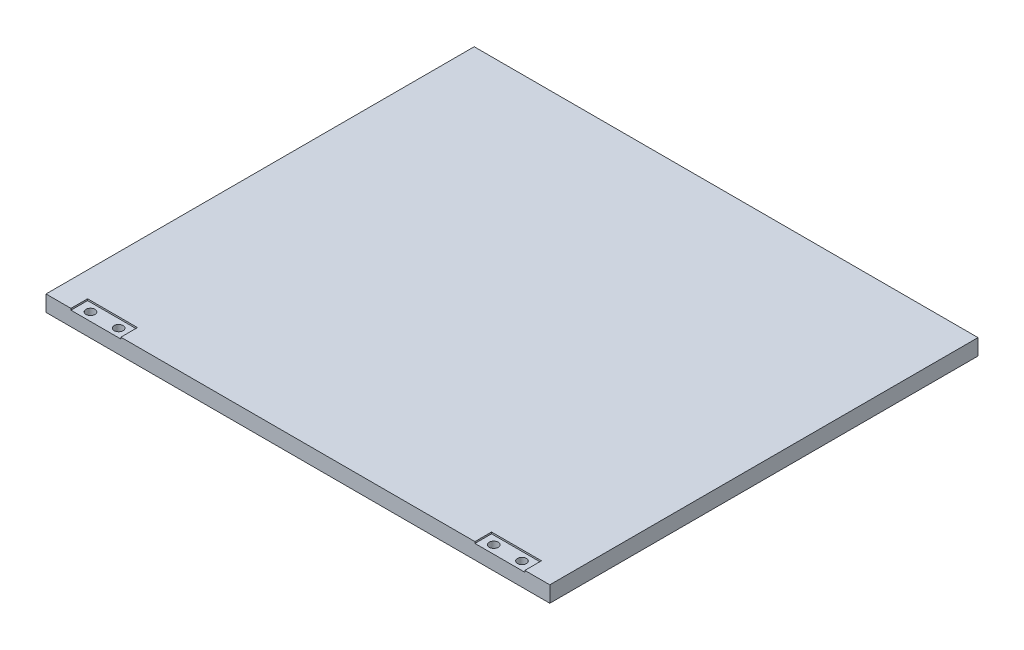
SolidWorks part; units mm, degrees
material "1023 Carbon Steel Sheet (SS)"
ref_plane "Front Plane" through (0, 0, 0) normal (0, 0, 1) x (1, 0, 0)
ref_plane "Top Plane" through (0, 0, 0) normal (0, 1, 0) x (1, 0, 0)
ref_plane "Right Plane" through (0, 0, 0) normal (1, 0, 0) x (0, 0, -1)
sketch "Sketch1" plane through (0, 0, 0) normal (0, 1, 0) x (1, 0, 0)
  line L1 (-100, -85) -> (100, -85)
  line L2 (-100, -85) -> (-100, 85)
  line L3 (-100, 85) -> (100, 85)
  line L4 (100, -85) -> (100, 85)
  line L5 (-100, -85) -> (100, 85) construction
  line L6 (-100, 85) -> (100, -85) construction
  point P0 (0, 0)
  dimension "D1" = 200
  dimension "D2" = 170
extrude "1/4\" Steel Plate" add sketch "Sketch1" along normal blind 6.35
ref_plane "Midplane" through (0, 0, 0) normal (-1, 0, 0) x (0, 0, 1)
sketch "Sketch2" plane through (0, 6.35, 0) normal (0, 1, 0) x (1, 0, 0)
  line L0 (-100, -85) -> (100, -85) construction
  line L1 (-90.094, -85) -> (-70.282, -85)
  line L2 (-90.094, -85) -> (-90.094, -78.396)
  line L3 (-90.094, -78.396) -> (-70.282, -78.396)
  line L4 (-70.282, -85) -> (-70.282, -78.396)
  line L5 (-100, 85) -> (-100, -85) construction
  dimension "D1" = 9.906
  dimension "D2" = 6.604
  dimension "D3" = 19.812
extrude "BladeHingeCut" cut sketch "Sketch2" against normal blind 0.635
hole_wizard "BladeHingeHole" positions "3DSketch2" profile "Sketch4" hole size "#8" standard "ANSI Inch" end condition through all
sketch3d "3DSketch2"
  line L0 (-90.094, 5.715, 85) -> (-70.282, 5.715, 85) construction
  line L1 (-90.094, 5.715, 78.396) -> (-90.094, 5.715, 85) construction
  line L2 (-70.282, 5.715, 85) -> (-70.282, 5.715, 78.396) construction
  point P0 (-74.473, 5.715, 81.698)
  point P2 (-85.649, 5.715, 81.698)
  dimension "D1" = 3.302
  dimension "D2" = 3.302
  dimension "D3" = 11.176
  dimension "D4" = 4.445
  dimension "D5" = 4.191
sketch "Sketch4" plane through (-74.473, 5.715, 81.698) normal (1, 0, 0) x (0, 0, 1)
  line L0 (0, 0) -> (0, 5.715)
  line L1 (0, 5.715) -> (1.778, 5.715)
  line L2 (1.778, 5.715) -> (1.778, 0)
  line L5 (1.778, 0) -> (0, 0)
  line L11 (0, -6.35) -> (0, 107.95) construction
  dimension "Thru Hole Dia." = 3.556
  dimension "Thru Hole Depth" = 5.715
sketch "Sketch5" plane through (0, 0, 0) normal (0, -1, 0) x (1, 0, 0)
  line L1 (-88.174, 79.173) -> (-83.124, 79.173)
  line L2 (-88.174, 79.173) -> (-88.174, 84.223)
  line L3 (-88.174, 84.223) -> (-83.124, 84.223)
  line L4 (-83.124, 79.173) -> (-83.124, 84.223)
  line L5 (-88.174, 79.173) -> (-83.124, 84.223) construction
  line L6 (-88.174, 84.223) -> (-83.124, 79.173) construction
  line L7 (-71.948, 79.173) -> (-76.998, 79.173)
  line L8 (-71.948, 79.173) -> (-71.948, 84.223)
  line L9 (-71.948, 84.223) -> (-76.998, 84.223)
  line L10 (-76.998, 79.173) -> (-76.998, 84.223)
  line L11 (-71.948, 79.173) -> (-76.998, 84.223) construction
  line L12 (-71.948, 84.223) -> (-76.998, 79.173) construction
  point P0 (-85.649, 81.698)
  point P6 (-74.473, 81.698)
  dimension "D1" = 5.05
  dimension "D2" = 5.05
  dimension "D3" = 5.05
  dimension "D4" = 5.05
extrude "BladeNutCut" cut sketch "Sketch5" against normal blind 2
mirror "BladeHingeMirror" about plane through (0, 0, 0) normal (-1, 0, 0) of "BladeNutCut", "BladeHingeHole", "BladeHingeCut"
